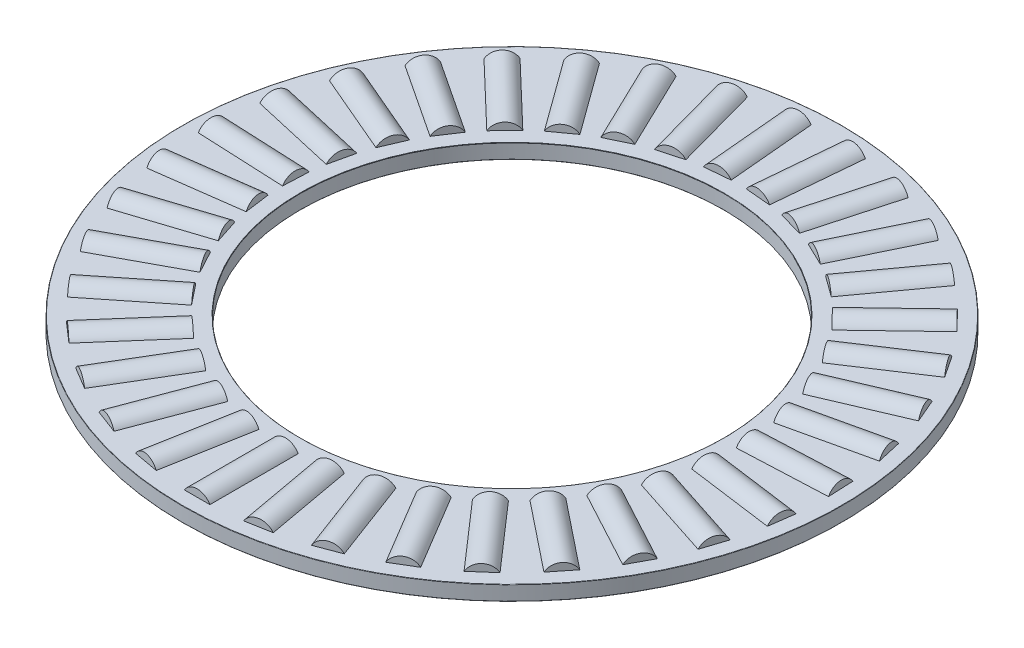
SolidWorks part; units mm, degrees
material "AISI 4130 Steel, normalized at 870C"
ref_plane "Front Plane" through (0, 0, 0) normal (0, 0, 1) x (1, 0, 0)
ref_plane "Top Plane" through (0, 0, 0) normal (0, 1, 0) x (1, 0, 0)
ref_plane "Right Plane" through (0, 0, 0) normal (1, 0, 0) x (0, 0, -1)
sketch "Sketch1" plane through (0, 0, 0) normal (1, 0, 0) x (0, 0, -1)
  line L0 (-22.225, 0) -> (22.225, 0) construction
  line L1 (0, -0.9922) -> (0, 0.9922) construction
  line L2 (-22.225, 0.4961) -> (-14.2875, 0.4961)
  line L3 (-22.225, 0.4961) -> (-22.225, -0.4961)
  line L4 (-22.225, -0.4961) -> (-14.2875, -0.4961)
  line L5 (-14.2875, 0.4961) -> (-14.2875, -0.4961)
  line L7 (-18.2563, 0.9922) -> (-18.2563, 0.4961) construction
  line L8 (-21.2328, 0.9922) -> (-15.2797, 0.9922) construction
  line L9 (-21.2328, 0.9922) -> (-21.2328, -0.9922) construction
  line L10 (-21.2328, -0.9922) -> (-15.2797, -0.9922) construction
  line L11 (-15.2797, 0.9922) -> (-15.2797, -0.9922) construction
  point P16 (-21.2328, 0)
  dimension "D1" = 5.9531
  dimension "OD" = 44.45
  dimension "Shaft Dia" = 28.575
  dimension "Th" = 1.9844
  dimension "D2" = 0.9922
  dimension "D3" = 7.9375
revolve "Revolve1" add sketch "Sketch1" angle 360 about L1
sketch "Sketch3" plane through (0, 0, 0) normal (1, 0, 0) x (0, 0, -1)
  line L0 (-21.2328, 0.9922) -> (-21.2328, -0.9922) construction
  line L1 (-21.2328, 0) -> (-15.2797, 0)
  line L2 (-21.2328, 0) -> (-21.2328, 0.9922)
  line L3 (-21.2328, 0.9922) -> (-15.2797, 0.9922)
  line L4 (-15.2797, 0) -> (-15.2797, 0.9922)
revolve "Cut-Revolve1" cut sketch "Sketch3" angle 360 about L1
sketch "Sketch2" plane through (0, 0, 0) normal (1, 0, 0) x (0, 0, -1)
  line L1 (-21.2328, 0) -> (-15.2797, 0)
  line L2 (-21.2328, 0) -> (-21.2328, 0.9922)
  line L3 (-21.2328, 0.9922) -> (-15.2797, 0.9922)
  line L4 (-15.2797, 0) -> (-15.2797, 0.9922)
revolve "Revolve2" add sketch "Sketch2" angle 360 about L1
ref_axis "Axis1" through (0, 0.9922, 0) along (0, -1, 0)
pattern_circular "CirPattern1" count 35 every 10.286 about axis through (0, 0.9922, 0) along (0, -1, 0) of bodies 187 411
pattern_circular "CirPattern2" count 35 every 10.286 about axis through (0, 0, 0) along (0, 1, 0) of "Cut-Revolve1"
sketch "Sketch4" plane through (0, 0, 0) normal (1, 0, 0) x (0, 0, -1)
  line L0 (-22.225, 0.4961) -> (-22.225, -0.4961) construction
  line L1 (-22.225, 9.1091) -> (-14.2875, 9.1091)
  line L2 (-22.225, 9.1091) -> (-22.225, 9.9219)
  line L3 (-22.225, 9.9219) -> (-14.2875, 9.9219)
  line L4 (-14.2875, 9.1091) -> (-14.2875, 9.9219)
  line L5 (-22.225, -9.9219) -> (-14.2875, -9.9219)
  line L6 (-22.225, -9.9219) -> (-22.225, -9.1091)
  line L7 (-22.225, -9.1091) -> (-14.2875, -9.1091)
  line L8 (-14.2875, -9.9219) -> (-14.2875, -9.1091)
  line L10 (-14.2875, 0.4961) -> (-14.2875, -0.4961) construction
  line L11 (0, 0) -> (-22.225, 0) construction
  line L12 (-22.225, 0) -> (22.225, 0) construction
  line L13 (0, -0.9922) -> (0, 0.9922) construction
  dimension "Ht" = 19.8438
  dimension "Washer Th" = 0.8128
  dimension "Washer ID" = 28.575
  dimension "Washer OD" = 44.45
revolve "Revolve3" [suppressed] add sketch "Sketch4" angle 360 about L1
fillet "Fillet1" [suppressed] radius 0.0198
fillet "Fillet2" radius 0.0198 4 edges at (0, -0.4961, -14.2875) (0, 0.4961, -14.2875) (0, -0.4961, -22.225) (0, 0.4961, -22.225)
fillet "Fillet3" [suppressed] radius 0.0198
equation "\"D2@Sketch1\" = \"Th@Sketch1\"*.5"
equation "\"D1@Fillet1\" = \"Th@Sketch1\"*.01"
equation "\"D1@Fillet2\" = \"D1@Fillet1\""
equation "\"D1@Fillet3\" = \"D1@Fillet1\""
equation "\"D1@Sketch1\" = \"D3@Sketch1\"*.75"
equation "\"Angle@CirPattern1\" = 360/\"Rollers@CirPattern1\""
equation "\"Rollers@CirPattern1\" = \"OD@Sketch1\"*20"
equation "\"D1@CirPattern2\" = \"Rollers@CirPattern1\""
equation "\"D2@CirPattern2\" = \"Angle@CirPattern1\""
equation "\"Ht@Sketch4\" = \"Th@Sketch1\"*10"
